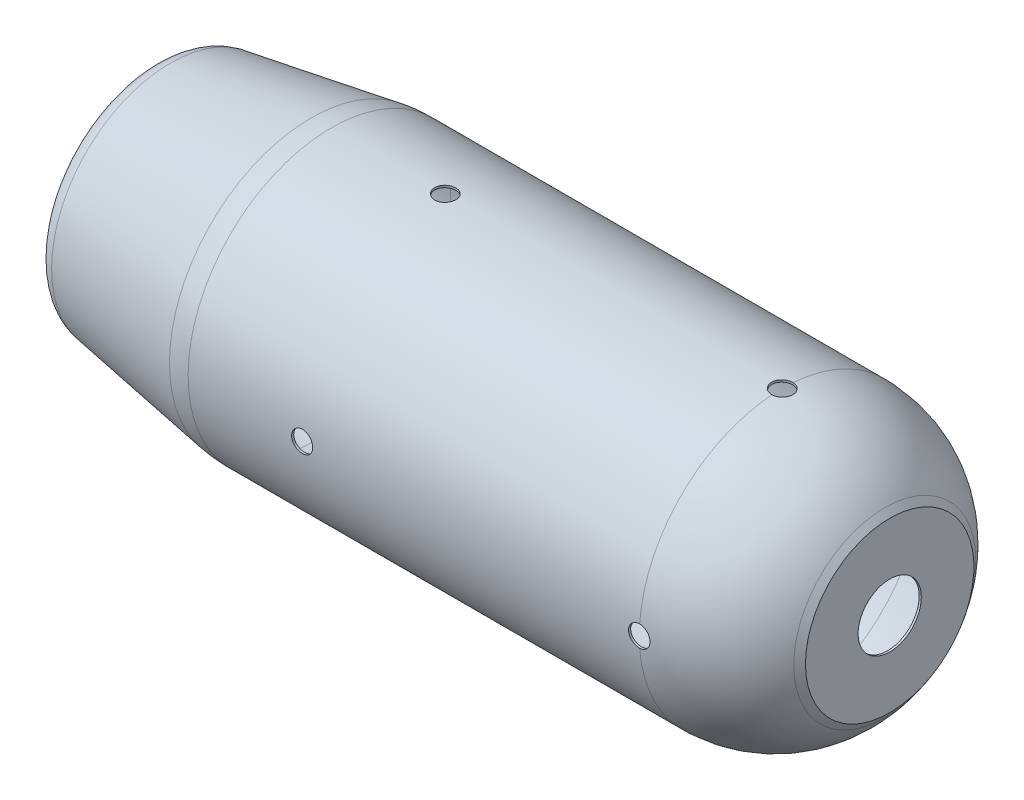
SolidWorks part; units mm, degrees
ref_plane "Front Plane" through (0, 0, 0) normal (0, 0, 1) x (1, 0, 0)
ref_plane "Top Plane" through (0, 0, 0) normal (0, 1, 0) x (1, 0, 0)
ref_plane "Right Plane" through (0, 0, 0) normal (1, 0, 0) x (0, 0, -1)
sketch "Sketch1" plane through (0, 0, 0) normal (0, 0, 1) x (1, 0, 0)
  line L0 (0, 0) -> (350, 0) construction
  line L1 (0, 0) -> (0, 55)
  line L2 (0, 55) -> (80, 68)
  line L3 (80, 68) -> (329.7024, 68)
  line L4 (329.7024, 68) -> (350, 40)
  line L5 (350, 40) -> (350, 0)
  line L6 (0, 0) -> (350, 0)
  dimension "D1" = 68
  dimension "D2" = 55
  dimension "D3" = 350
  dimension "D4" = 40
  dimension "D5" = 80
revolve "Revolve1" add sketch "Sketch1" angle 360 about L0
fillet "Fillet1" radius 60 2 edges at (329.7024, 0, 68) (80, 0, 68)
fillet "Fillet2" radius 10 1 edges at (0, 0, 55)
shell "Shell2" thickness 1
sketch "Sketch3" plane through (0, 0, 0) normal (-1, 0, 0) x (0, 0, 1)
  circle A0 centre (0, 0) radius 1.5
  dimension "D1" = 3
extrude "Cut-Extrude1" cut sketch "Sketch3" against normal blind 10
sketch "Sketch4" plane through (0, 0, 0) normal (-1, 0, 0) x (0, 0, 1)
  line L0 (0, 0) -> (30.3938, 0) construction
  line L1 (0, 0) -> (28.2843, 28.2843) construction
  circle A0 centre (28.2843, 28.2843) radius 3
  circle A1 centre (28.2843, -28.2843) radius 3
  circle A2 centre (-28.2843, -28.2843) radius 3
  circle A3 centre (-28.2843, 28.2843) radius 3
  point P15 (0, 0)
  dimension "D2" = 6
  dimension "D1" = 40
  dimension "D3" = 45
  dimension "D4" = 4
extrude "Cut-Extrude2" cut sketch "Sketch4" against normal blind 10
sketch "Sketch5" plane through (0, 0, 0) normal (0, 0, 1) x (1, 0, 0)
  circle A0 centre (139, 0) radius 5
  circle A1 centre (299, 0) radius 5
  dimension "D3" = 10
  dimension "D1" = 139
  dimension "D2" = 160
extrude "Cut-Extrude3" cut sketch "Sketch5" against normal blind 90
pattern_circular "CirPattern1" count 4 over 360 about axis through (80, 0, 0) along (1, 0, 0) of "Cut-Extrude3"
sketch "Sketch6" plane through (350, 0, 0) normal (1, 0, 0) x (0, 0, -1)
  circle A0 centre (0, 0) radius 15
  dimension "D1" = 30
extrude "Cut-Extrude4" cut sketch "Sketch6" against normal blind 10
